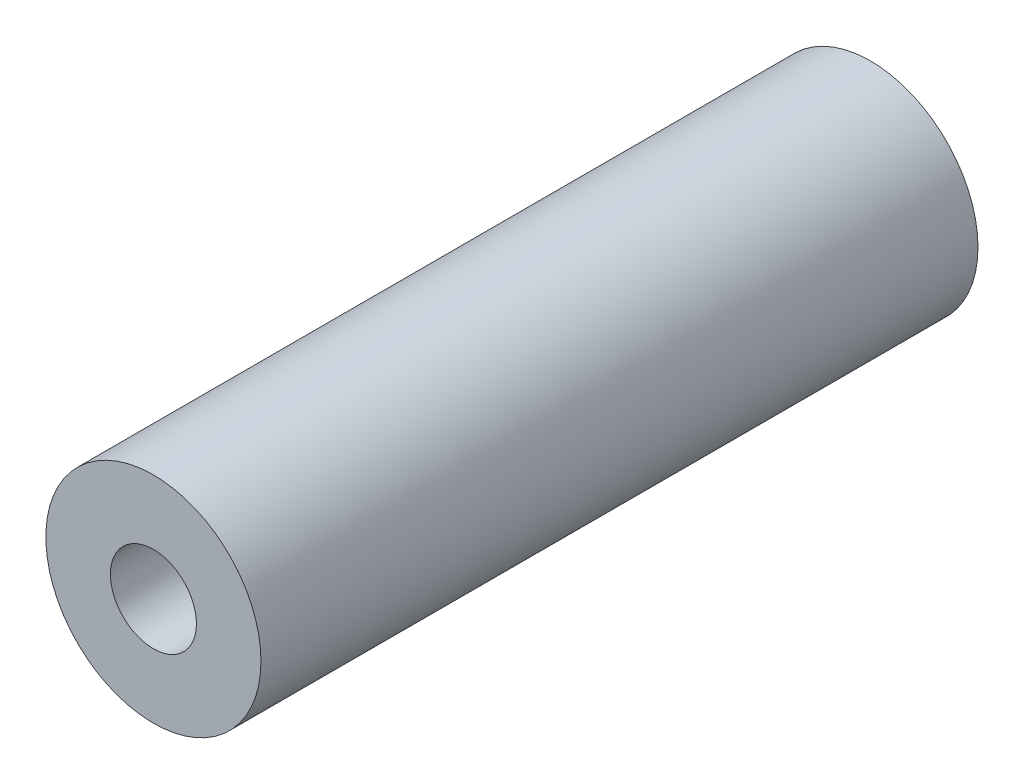
SolidWorks part; units mm, degrees
ref_plane "Alzado" through (0, 0, 0) normal (0, 0, 1) x (1, 0, 0)
ref_plane "Planta" through (0, 0, 0) normal (0, 1, 0) x (1, 0, 0)
ref_plane "Vista lateral" through (0, 0, 0) normal (1, 0, 0) x (0, 0, -1)
sketch "Croquis1" plane through (0, 0, 0) normal (0, 0, 1) x (1, 0, 0)
  circle A0 centre (0, 0) radius 2.25
  circle A1 centre (0, 0) radius 0.99
  dimension "D1" = 4.5
  dimension "D2" = 1.98
extrude "Saliente-Extruir1" add sketch "Croquis1" along normal blind 15
sketch "Croquis2" plane through (0, 0, 15) normal (0, 0, 1) x (1, 0, 0)
  circle A0 centre (0, 0) radius 1.3677
  circle A1 centre (0, 0) radius 0.9
  dimension "D1" = 2.7353
  dimension "D2" = 1.8
extrude "Saliente-Extruir2" add sketch "Croquis2" against normal blind 5
